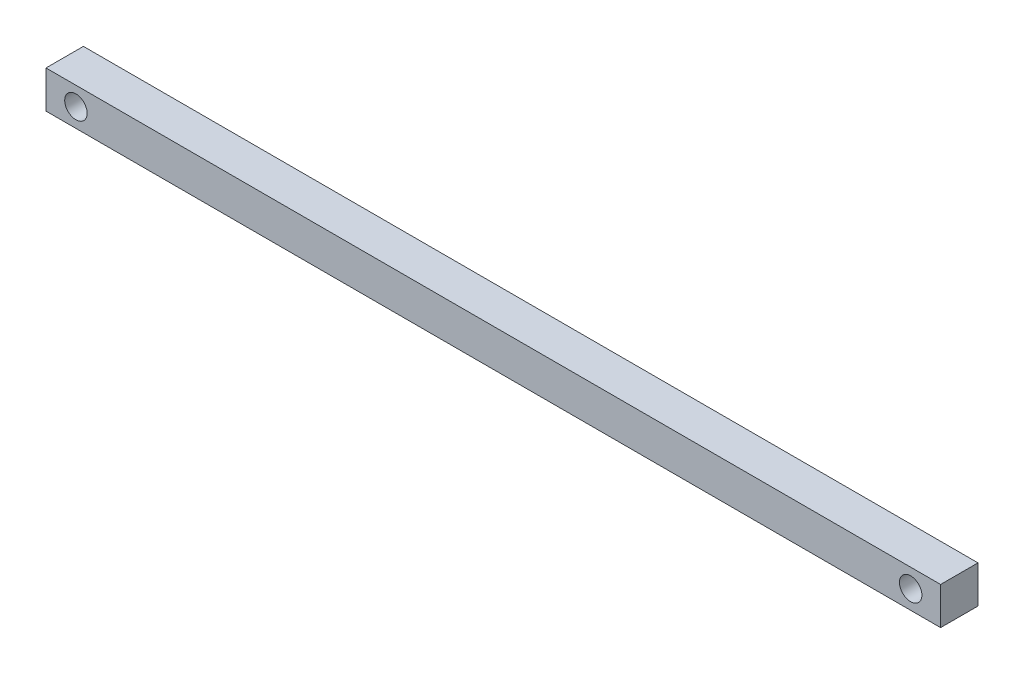
SolidWorks part; units mm, degrees
ref_plane "Front Plane" through (0, 0, 0) normal (0, 0, 1) x (1, 0, 0)
ref_plane "Top Plane" through (0, 0, 0) normal (0, 1, 0) x (1, 0, 0)
ref_plane "Right Plane" through (0, 0, 0) normal (1, 0, 0) x (0, 0, -1)
sketch "Sketch1" plane through (0, 0, 0) normal (0, 0, 1) x (1, 0, 0)
  line L0 (-480.2841, 0) -> (504.376, 0) construction
  line L1 (0, 257.2396) -> (0, -306.2006) construction
  line L3 (-299, 12.5) -> (299, 12.5)
  line L4 (-299, 12.5) -> (-299, -12.5)
  line L5 (-299, -12.5) -> (299, -12.5)
  line L6 (299, 12.5) -> (299, -12.5)
  line L7 (-299, 12.5) -> (299, -12.5) construction
  line L8 (-299, -12.5) -> (299, 12.5) construction
  point P5 (0, 0)
  dimension "D1" = 598
  dimension "D2" = 25
extrude "Boss-Extrude1" add sketch "Sketch1" along normal blind 25
sketch "Sketch2" plane through (0, 0, 25) normal (0, 0, 1) x (1, 0, 0)
  circle A0 centre (-279, 0) radius 7.5
  circle A1 centre (279, 0) radius 7.5
  dimension "D3" = 15
  dimension "D4" = 15
  dimension "D1" = 279
  dimension "D2" = 279
extrude "Cut-Extrude1" cut sketch "Sketch2" against normal through all both and the other way through all
